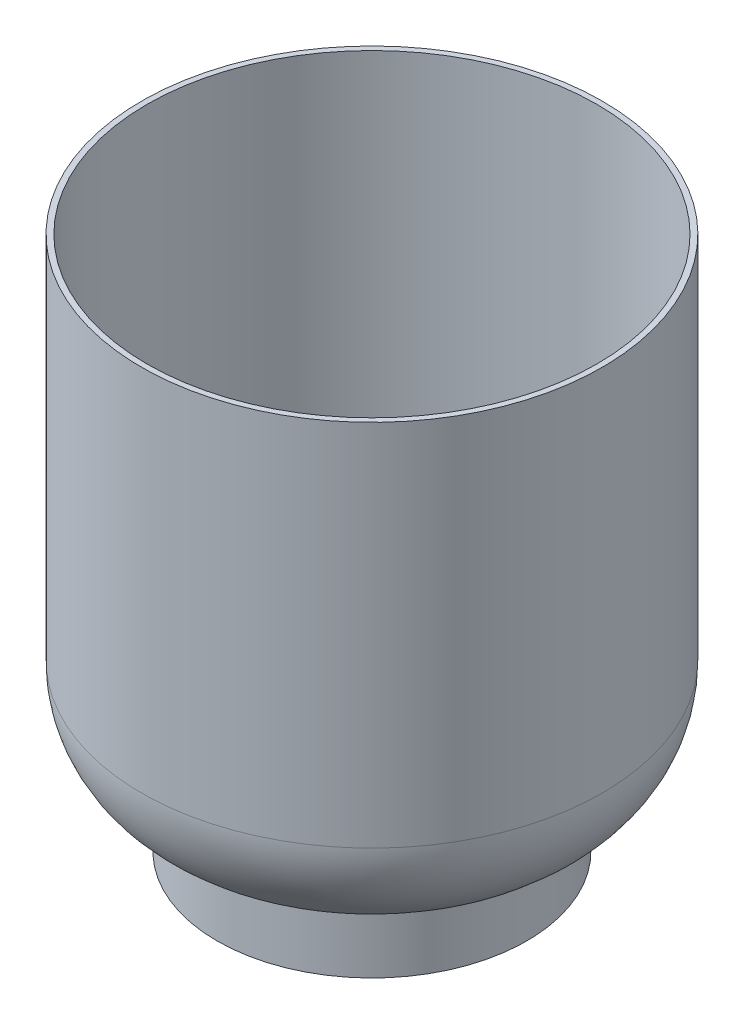
SolidWorks part; units mm, degrees
ref_plane "Ön Düzlem" through (0, 0, 0) normal (0, 0, 1) x (1, 0, 0)
ref_plane "Üst Düzlem" through (0, 0, 0) normal (0, 1, 0) x (1, 0, 0)
ref_plane "Sağ Düzlem" through (0, 0, 0) normal (1, 0, 0) x (0, 0, -1)
sketch "Çizim1" plane through (0, 0, 0) normal (0, 0, 1) x (1, 0, 0)
  line L0 (0, 0) -> (0, 200) construction
  line L1 (-62.5, 80.5133) -> (-62.5, -19.4867)
  line L2 (-42, -49.0036) -> (-42, -64.4867)
  line L3 (-61, 80.5133) -> (-61, -19.4867)
  line L4 (-40.5, -47.9428) -> (-40.5, -54.4867)
  line L5 (-42, -64.4867) -> (-40.5, -64.4867)
  line L6 (-62.5, 80.5133) -> (-61, 80.5133)
  line L7 (-40.5, -58.4867) -> (-34.5, -58.4867)
  line L8 (-34.5, -58.4867) -> (-34.5, -54.4867)
  line L9 (-34.5, -54.4867) -> (-40.5, -54.4867)
  line L10 (-42, -47.9428) -> (-42, -64.4867) construction
  line L11 (-40.5, -46.8408) -> (-40.5, -64.4867) construction
  line L12 (-40.5, -58.4867) -> (-40.5, -64.4867)
  arc A0 (-62.5, -19.4867) -> (-42.9762, -47.598) centre (-32.5, -19.4867) ccw
  arc A1 (-61, -19.4867) -> (-41.525, -46.52) centre (-32.5, -19.4867) ccw
  arc A2 (-62.5, -19.4867) -> (-42, -47.9428) centre (-32.5, -19.4867) ccw construction
  arc A3 (-42, -49.0036) -> (-42.9762, -47.598) centre (-43.5, -49.0036) ccw
  arc A4 (-61, -19.4867) -> (-40.5, -46.8408) centre (-32.5, -19.4867) ccw construction
  arc A5 (-41.525, -46.52) -> (-40.5, -47.9428) centre (-42, -47.9428) cw
  point P16 (-42, -47.9428)
  point P24 (0, 0)
  point P26 (0, 0)
  dimension "D8" = 60
  dimension "D13" = 1.5
  dimension "D2" = 100
  dimension "D3" = 200
  dimension "D4" = 16.5439
  dimension "D7" = 145
  dimension "D9" = 1.5
  dimension "D10" = 6
  dimension "D11" = 4
  dimension "D12" = 10
revolve "Döndür5" add sketch "Çizim1" angle 360 about L0
